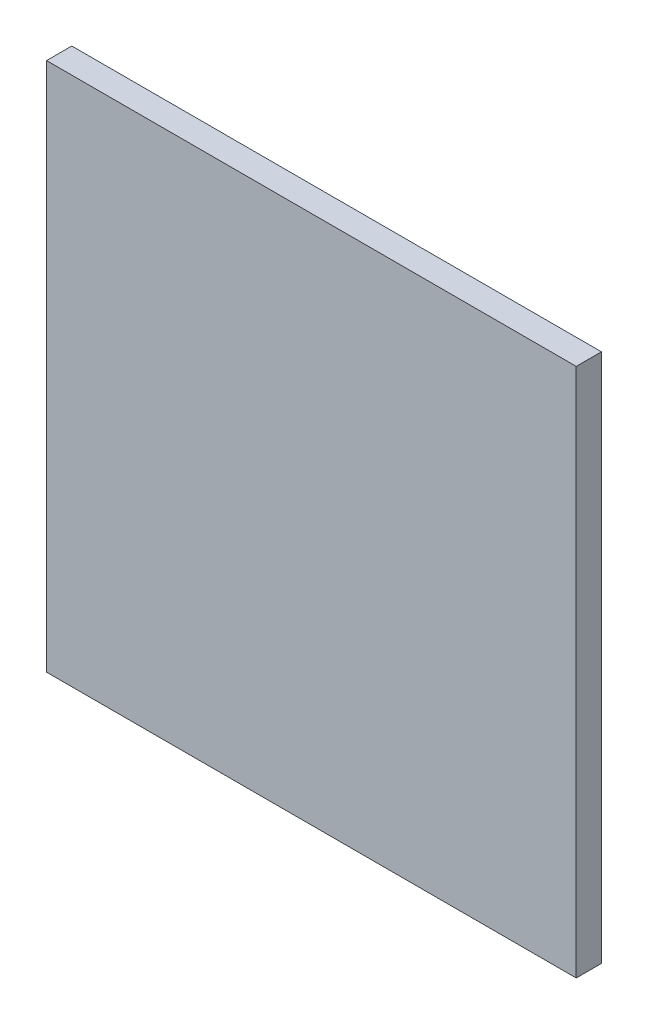
SolidWorks part; units mm, degrees
material "PMMA"
ref_plane "Front Plane" through (0, 0, 0) normal (0, 0, 1) x (1, 0, 0)
ref_plane "Top Plane" through (0, 0, 0) normal (0, 1, 0) x (1, 0, 0)
ref_plane "Right Plane" through (0, 0, 0) normal (1, 0, 0) x (0, 0, -1)
sketch "Sketch1" plane through (0, 0, 0) normal (0, 0, 1) x (1, 0, 0)
  line L1 (-52.5, 105) -> (52.5, 105)
  line L2 (-52.5, 105) -> (-52.5, 0)
  line L3 (-52.5, 0) -> (52.5, 0)
  line L4 (52.5, 105) -> (52.5, 0)
  point P4 (0, 0)
  dimension "D2" = 105
extrude "Boss-Extrude1" add sketch "Sketch1" along normal blind 5
